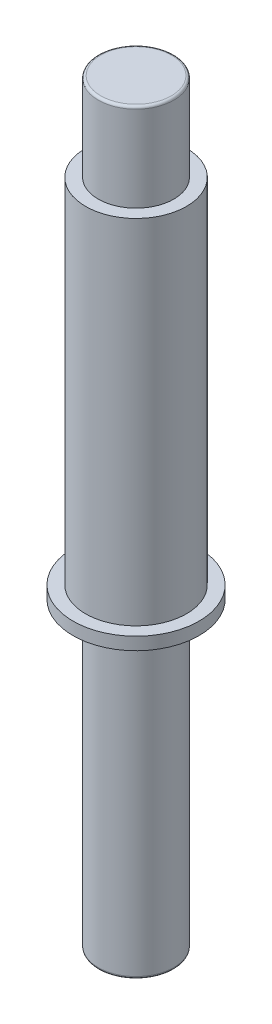
SolidWorks part; units mm, degrees
ref_plane "前视基准面" through (0, 0, 0) normal (0, 0, 1) x (1, 0, 0)
ref_plane "上视基准面" through (0, 0, 0) normal (0, 1, 0) x (1, 0, 0)
ref_plane "右视基准面" through (0, 0, 0) normal (1, 0, 0) x (0, 0, -1)
sketch "草图1" plane through (0, 0, 0) normal (0, 1, 0) x (1, 0, 0)
  circle A0 centre (0, 0) radius 1.5
extrude "凸台-拉伸1" add sketch "草图1" along normal blind 30
ref_plane "基准面1" through (0, 12, 0) normal (0, 1, 0) x (1, 0, 0)
sketch "草图2" plane through (0, 12, 0) normal (0, 1, 0) x (1, 0, 0)
  circle A0 centre (0, 0) radius 2
  circle A1 centre (0, 0) radius 1.5
extrude "凸台-拉伸2" add sketch "草图2" along normal blind 14.5
fillet "圆角1" radius 0.1 2 edges at (0, 30, 1.5) (0, 0, 1.5)
sketch "草图3" plane through (0, 12, 0) normal (0, -1, 0) x (-1, 0, 0)
  circle A0 centre (0, 0) radius 2
  circle A1 centre (0, 0) radius 2.5
extrude "凸台-拉伸3" add sketch "草图3" against normal blind 0.5
